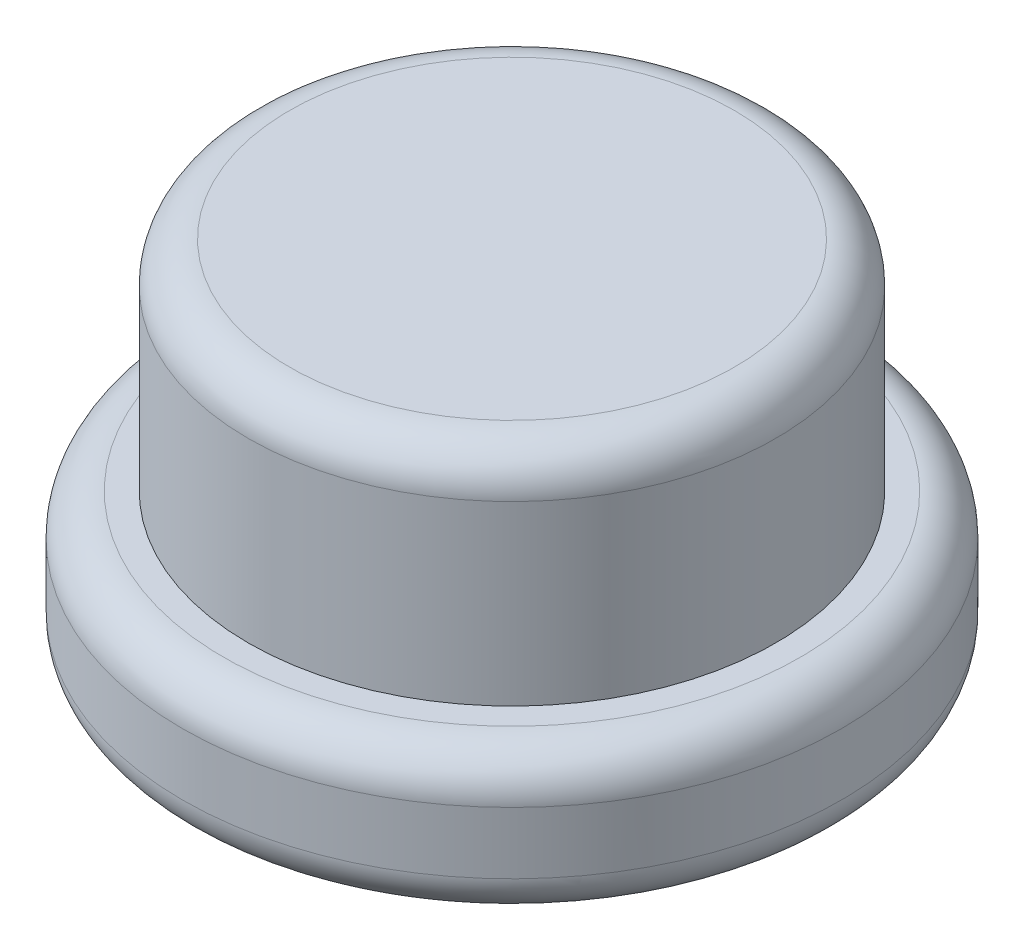
SolidWorks part; units mm, degrees
ref_plane "Plan de face" through (0, 0, 0) normal (0, 0, 1) x (1, 0, 0)
ref_plane "Plan de dessus" through (0, 0, 0) normal (0, 1, 0) x (1, 0, 0)
ref_plane "Plan de droite" through (0, 0, 0) normal (1, 0, 0) x (0, 0, -1)
sketch "Esquisse1" plane through (0, 0, 0) normal (0, 0, 1) x (1, 0, 0)
  line L0 (0, 10) -> (0, 0) construction
  line L1 (3, 1.2) -> (8, 1.2)
  line L2 (8, 1.2) -> (8, 4.7)
  line L3 (8, 4.7) -> (6.4, 4.7)
  line L4 (6.4, 4.7) -> (6.4, 10)
  line L5 (6.4, 10) -> (0, 10)
  line L6 (0, 10) -> (0, 0)
  arc A0 (0, 0) -> (3, 1.2) centre (0, 4.35) ccw
  dimension "D1" = 10
  dimension "D4" = 16
  dimension "D2" = 8.8
  dimension "D3" = 6
  dimension "D5" = 12.8
  dimension "D6" = 5.3
revolve "Révolution1" add sketch "Esquisse1" angle 360 about L0
fillet "Congé1" radius 1 3 edges at (0, 1.2, 8) (0, 4.7, 8) (0, 10, 6.4)
